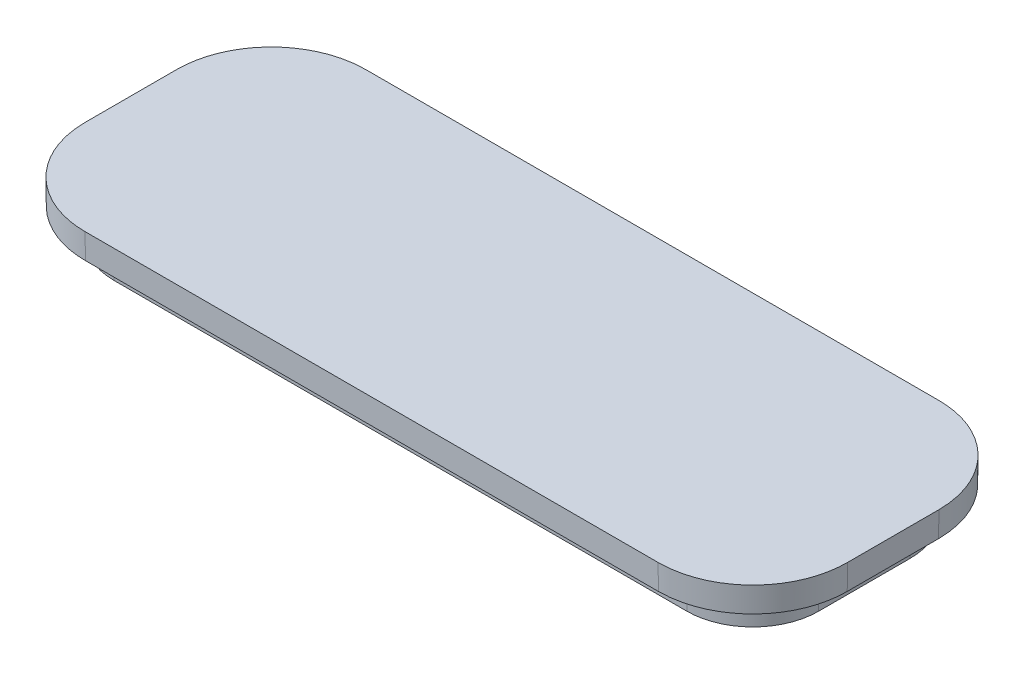
SolidWorks part; units mm, degrees
ref_plane "Front Plane" through (0, 0, 0) normal (0, 0, 1) x (1, 0, 0)
ref_plane "Top Plane" through (0, 0, 0) normal (0, 1, 0) x (1, 0, 0)
ref_plane "Right Plane" through (0, 0, 0) normal (1, 0, 0) x (0, 0, -1)
sketch "Sketch1" plane through (0, 0, 0) normal (0, 1, 0) x (1, 0, 0)
  line L1 (-11.8, -4.15) -> (11.8, -4.15)
  line L2 (-11.8, -4.15) -> (-11.8, 4.15)
  line L3 (-11.8, 4.15) -> (11.8, 4.15)
  line L4 (11.8, -4.15) -> (11.8, 4.15)
  line L5 (-11.8, -4.15) -> (11.8, 4.15) construction
  line L6 (-11.8, 4.15) -> (11.8, -4.15) construction
  point P0 (0, 0)
  dimension "D1" = 23.6
  dimension "D2" = 8.3
extrude "Boss-Extrude1" add sketch "Sketch1" along normal blind 34.6 draft 0.5 draft outward yes
fillet "Fillet1" radius 3 4 edges at (-11.951, 17.3, -4.301) (11.951, 17.3, -4.301) (11.951, 17.3, 4.301) (-11.951, 17.3, 4.301)
sketch "Sketch2" plane through (0, 34.6, 0) normal (0, 1, 0) x (1, 0, 0)
  line L8 (9.1021, 4.4519) -> (-9.1021, 4.4519)
  line L9 (-12.1019, 1.4521) -> (-12.1019, -1.4521)
  line L10 (-9.1021, -4.4519) -> (9.1021, -4.4519)
  line L11 (12.1019, -1.4521) -> (12.1019, 1.4521)
  line L12 (9.1021, 4.4519) -> (-9.1021, 4.4519)
  line L13 (-12.1019, 1.4521) -> (-12.1019, -1.4521)
  line L14 (-9.1021, -4.4519) -> (9.1021, -4.4519)
  line L15 (12.1019, -1.4521) -> (12.1019, 1.4521)
  ellipse E8 centre (-9.1018, 1.4518) end of major axis (-6.9804, -0.6696) minor radius 3 (-9.1021, 4.4519) -> (-12.1019, 1.4521) ccw
  ellipse E9 centre (-9.1018, -1.4518) end of major axis (-11.2233, -3.5733) minor radius 3 (-12.1019, -1.4521) -> (-9.1021, -4.4519) ccw
  ellipse E10 centre (9.1018, -1.4518) end of major axis (6.9804, 0.6696) minor radius 3 (9.1021, -4.4519) -> (12.1019, -1.4521) ccw
  ellipse E11 centre (9.1018, 1.4518) end of major axis (6.9804, -0.6696) minor radius 3 (12.1019, 1.4521) -> (9.1021, 4.4519) ccw
  ellipse E12 centre (-9.1018, 1.4518) end of major axis (-6.9804, -0.6696) minor radius 3 (-9.1021, 4.4519) -> (-12.1019, 1.4521) ccw
  ellipse E13 centre (-9.1018, -1.4518) end of major axis (-11.2233, -3.5733) minor radius 3 (-12.1019, -1.4521) -> (-9.1021, -4.4519) ccw
  ellipse E14 centre (9.1018, -1.4518) end of major axis (6.9804, 0.6696) minor radius 3 (9.1021, -4.4519) -> (12.1019, -1.4521) ccw
  ellipse E15 centre (9.1018, 1.4518) end of major axis (6.9804, -0.6696) minor radius 3 (12.1019, 1.4521) -> (9.1021, 4.4519) ccw
  dimension "D1" = 0
extrude "Boss-Extrude2" add sketch "Sketch2" along normal blind 0.8 draft 0.5 separate body
delete or keep bodies "Body-Delete1" type delete bodies bodies 101
sketch "Sketch3" plane through (0, 34.6, 0) normal (0, -1, 0) x (1, 0, 0)
  line L4 (-9.1021, -2.6519) -> (9.1021, -2.6519)
  line L5 (10.3019, -1.4521) -> (10.3019, 1.4521)
  line L6 (9.1021, 2.6519) -> (-9.1021, 2.6519)
  line L7 (-10.3019, 1.4521) -> (-10.3019, -1.4521)
  line L8 (11.2019, -1.4521) -> (11.2019, 1.4521)
  line L9 (9.1021, 3.5519) -> (-9.1021, 3.5519)
  line L10 (-11.2019, 1.4521) -> (-11.2019, -1.4521)
  line L11 (-9.1021, -3.5519) -> (9.1021, -3.5519)
  line L12 (11.2019, -1.4521) -> (11.2019, 1.4521)
  line L13 (9.1021, 3.5519) -> (-9.1021, 3.5519)
  line L14 (-11.2019, 1.4521) -> (-11.2019, -1.4521)
  line L15 (-9.1021, -3.5519) -> (9.1021, -3.5519)
  spline S4 degree 1 poles (9.1021, -2.6519) (10.3019, -1.4521) knots 0 0 1 1 construction
  spline S5 degree 1 poles (10.3019, 1.4521) (9.1021, 2.6519) knots 0 0 1 1 construction
  spline S6 degree 1 poles (-9.1021, 2.6519) (-10.3019, 1.4521) knots 0 0 1 1 construction
  spline S7 degree 1 poles (-10.3019, -1.4521) (-9.1021, -2.6519) knots 0 0 1 1 construction
  spline S8 degree 3 poles (-373.138, 1959.3641) (-51.6864, 165.7648) (-6.1531, -6.6237) (9.6454, -3.4849) (9.7788, -3.4447) (10.033, -3.3394) (10.1534, -3.2748) (10.3816, -3.1225) (10.4898, -3.034) (10.7802, -2.7437) (10.9367, -2.5097) (15.7674, 9.1258) (-79.3439, 67.5374) (-881.1913, -1789.1542) knots -14.470356 -14.470356 -14.470356 -14.470356 0.125 0.125 0.25 0.25 0.375 0.375 0.5 0.5 0.75 0.75 12.024599 12.024599 12.024599 12.024599 only from (9.1021, -3.5519) to (11.2019, -1.4521)
  spline S9 degree 3 poles (-1951.7141, -380.788) (-158.1148, -59.3364) (14.2737, -13.8031) (11.1349, 1.9954) (11.0947, 2.1288) (10.9894, 2.383) (10.9248, 2.5034) (10.7725, 2.7316) (10.684, 2.8398) (10.3937, 3.1302) (10.1597, 3.2867) (-1.4758, 8.1174) (-59.8874, -86.9939) (1796.8042, -888.8413) knots -14.470356 -14.470356 -14.470356 -14.470356 0.125 0.125 0.25 0.25 0.375 0.375 0.5 0.5 0.75 0.75 12.024599 12.024599 12.024599 12.024599 only from (11.2019, 1.4521) to (9.1021, 3.5519)
  spline S10 degree 3 poles (373.138, -1959.3641) (51.6864, -165.7648) (6.1531, 6.6237) (-9.6454, 3.4849) (-9.7788, 3.4447) (-10.033, 3.3394) (-10.1534, 3.2748) (-10.3816, 3.1225) (-10.4898, 3.034) (-10.7802, 2.7437) (-10.9367, 2.5097) (-15.7674, -9.1258) (79.3439, -67.5374) (881.1913, 1789.1542) knots -14.470356 -14.470356 -14.470356 -14.470356 0.125 0.125 0.25 0.25 0.375 0.375 0.5 0.5 0.75 0.75 12.024599 12.024599 12.024599 12.024599 only from (-9.1021, 3.5519) to (-11.2019, 1.4521)
  spline S11 degree 3 poles (1951.7141, 380.788) (158.1148, 59.3364) (-14.2737, 13.8031) (-11.1349, -1.9954) (-11.0947, -2.1288) (-10.9894, -2.383) (-10.9248, -2.5034) (-10.7725, -2.7316) (-10.684, -2.8398) (-10.3937, -3.1302) (-10.1597, -3.2867) (1.4758, -8.1174) (59.8874, 86.9939) (-1796.8042, 888.8413) knots -14.470356 -14.470356 -14.470356 -14.470356 0.125 0.125 0.25 0.25 0.375 0.375 0.5 0.5 0.75 0.75 12.024599 12.024599 12.024599 12.024599 only from (-11.2019, -1.4521) to (-9.1021, -3.5519)
  spline S12 degree 3 poles (9.1021, -3.5519) (9.2408, -3.5519) (9.3771, -3.5382) (9.6454, -3.4849) (9.7788, -3.4447) (10.033, -3.3394) (10.1534, -3.2748) (10.3816, -3.1225) (10.4898, -3.034) (10.7802, -2.7437) (10.9367, -2.5097) (11.1462, -2.0048) (11.2019, -1.7293) (11.2019, -1.4521) knots 0 0 0 0 0.125 0.125 0.25 0.25 0.375 0.375 0.5 0.5 0.75 0.75 1 1 1 1
  spline S13 degree 3 poles (11.2019, 1.4521) (11.2019, 1.5908) (11.1882, 1.7271) (11.1349, 1.9954) (11.0947, 2.1288) (10.9894, 2.383) (10.9248, 2.5034) (10.7725, 2.7316) (10.684, 2.8398) (10.3937, 3.1302) (10.1597, 3.2867) (9.6548, 3.4962) (9.3793, 3.5519) (9.1021, 3.5519) knots 0 0 0 0 0.125 0.125 0.25 0.25 0.375 0.375 0.5 0.5 0.75 0.75 1 1 1 1
  spline S14 degree 3 poles (-9.1021, 3.5519) (-9.2408, 3.5519) (-9.3771, 3.5382) (-9.6454, 3.4849) (-9.7788, 3.4447) (-10.033, 3.3394) (-10.1534, 3.2748) (-10.3816, 3.1225) (-10.4898, 3.034) (-10.7802, 2.7437) (-10.9367, 2.5097) (-11.1462, 2.0048) (-11.2019, 1.7293) (-11.2019, 1.4521) knots 0 0 0 0 0.125 0.125 0.25 0.25 0.375 0.375 0.5 0.5 0.75 0.75 1 1 1 1
  spline S15 degree 3 poles (-11.2019, -1.4521) (-11.2019, -1.5908) (-11.1882, -1.7271) (-11.1349, -1.9954) (-11.0947, -2.1288) (-10.9894, -2.383) (-10.9248, -2.5034) (-10.7725, -2.7316) (-10.684, -2.8398) (-10.3937, -3.1302) (-10.1597, -3.2867) (-9.6548, -3.4962) (-9.3793, -3.5519) (-9.1021, -3.5519) knots 0 0 0 0 0.125 0.125 0.25 0.25 0.375 0.375 0.5 0.5 0.75 0.75 1 1 1 1
  spline S16 degree 3 poles (9.1021, -2.6519) (9.4081, -2.6519) (10.0456, -2.3963) (10.3019, -1.7583) (10.3019, -1.4521) knots 0 0 0 0 0.5 1 1 1 1
  spline S17 degree 3 poles (10.3019, 1.4521) (10.3019, 1.7581) (10.0463, 2.3956) (9.4083, 2.6519) (9.1021, 2.6519) knots 0 0 0 0 0.5 1 1 1 1
  spline S18 degree 3 poles (-9.1021, 2.6519) (-9.4081, 2.6519) (-10.0456, 2.3963) (-10.3019, 1.7583) (-10.3019, 1.4521) knots 0 0 0 0 0.5 1 1 1 1
  spline S19 degree 3 poles (-10.3019, -1.4521) (-10.3019, -1.7581) (-10.0463, -2.3956) (-9.4083, -2.6519) (-9.1021, -2.6519) knots 0 0 0 0 0.5 1 1 1 1
  dimension "D1" = 0.9
  dimension "D2" = 0.9
extrude "Boss-Extrude3" add sketch "Sketch3" along normal blind 1 draft 0.5
fillet "Fillet2" radius 0.5 8 edges at (-9.8558, 34.6, 2.3852) (0, 34.6, 2.6519) (10.0352, 34.6, 2.2058) (10.3019, 34.6, 0) (9.8558, 34.6, -2.3852) (0, 34.6, -2.6519) (-10.0352, 34.6, -2.2058) (-10.3019, 34.6, 0)
